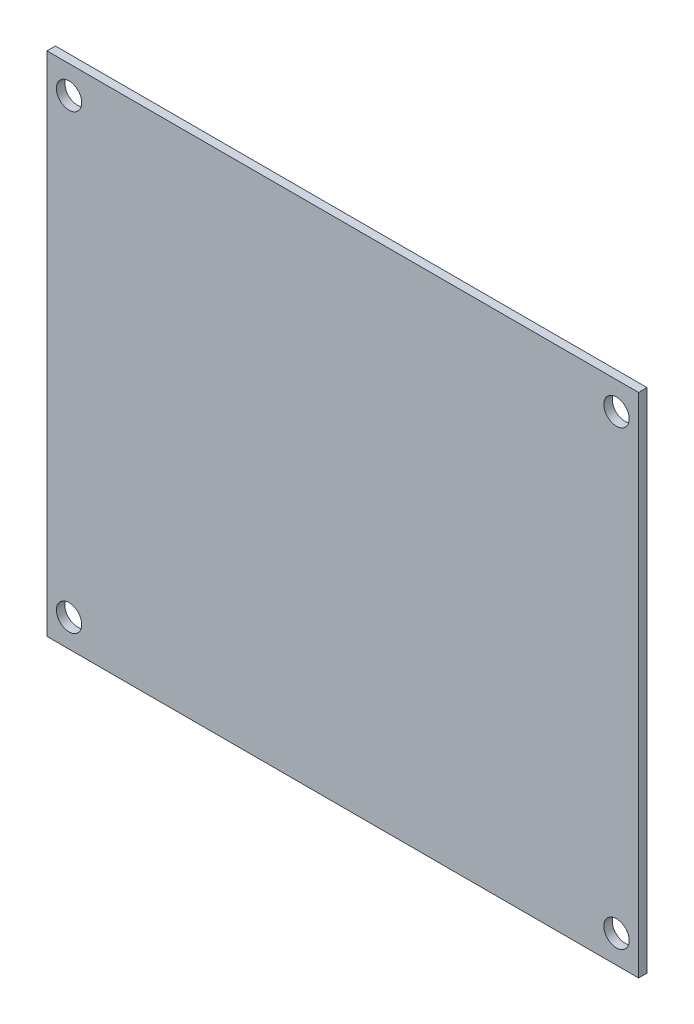
SolidWorks part; units mm, degrees
ref_plane "Plano frontal" through (0, 0, 0) normal (0, 0, 1) x (1, 0, 0)
ref_plane "Plano superior" through (0, 0, 0) normal (0, 1, 0) x (1, 0, 0)
ref_plane "Plano direito" through (0, 0, 0) normal (1, 0, 0) x (0, 0, -1)
sketch "Esboço1" plane through (0, 0, 0) normal (0, 0, 1) x (1, 0, 0)
  line L1 (-35, 30) -> (35, 30)
  line L2 (-35, 30) -> (-35, -30)
  line L3 (-35, -30) -> (35, -30)
  line L4 (35, 30) -> (35, -30)
  line L5 (-35, 30) -> (35, -30) construction
  line L6 (-35, -30) -> (35, 30) construction
  line L7 (32.385, 26.73) -> (-32.385, 26.73) construction
  line L8 (32.385, 26.73) -> (32.385, -26.73) construction
  line L9 (32.385, -26.73) -> (-32.385, -26.73) construction
  line L10 (-32.385, 26.73) -> (-32.385, -26.73) construction
  line L11 (32.385, 26.73) -> (-32.385, -26.73) construction
  line L12 (32.385, -26.73) -> (-32.385, 26.73) construction
  circle A0 centre (-32.385, 26.73) radius 1.5
  circle A1 centre (-32.385, -26.73) radius 1.5
  circle A2 centre (32.385, -26.73) radius 1.5
  circle A3 centre (32.385, 26.73) radius 1.5
  point P0 (0, 0)
  point P6 (0, 0)
  dimension "D5" = 3
  dimension "D1" = 60
  dimension "D2" = 70
  dimension "D3" = 64.77
  dimension "D4" = 53.46
extrude "Ressalto-extrusão1" add sketch "Esboço1" along normal blind 1
